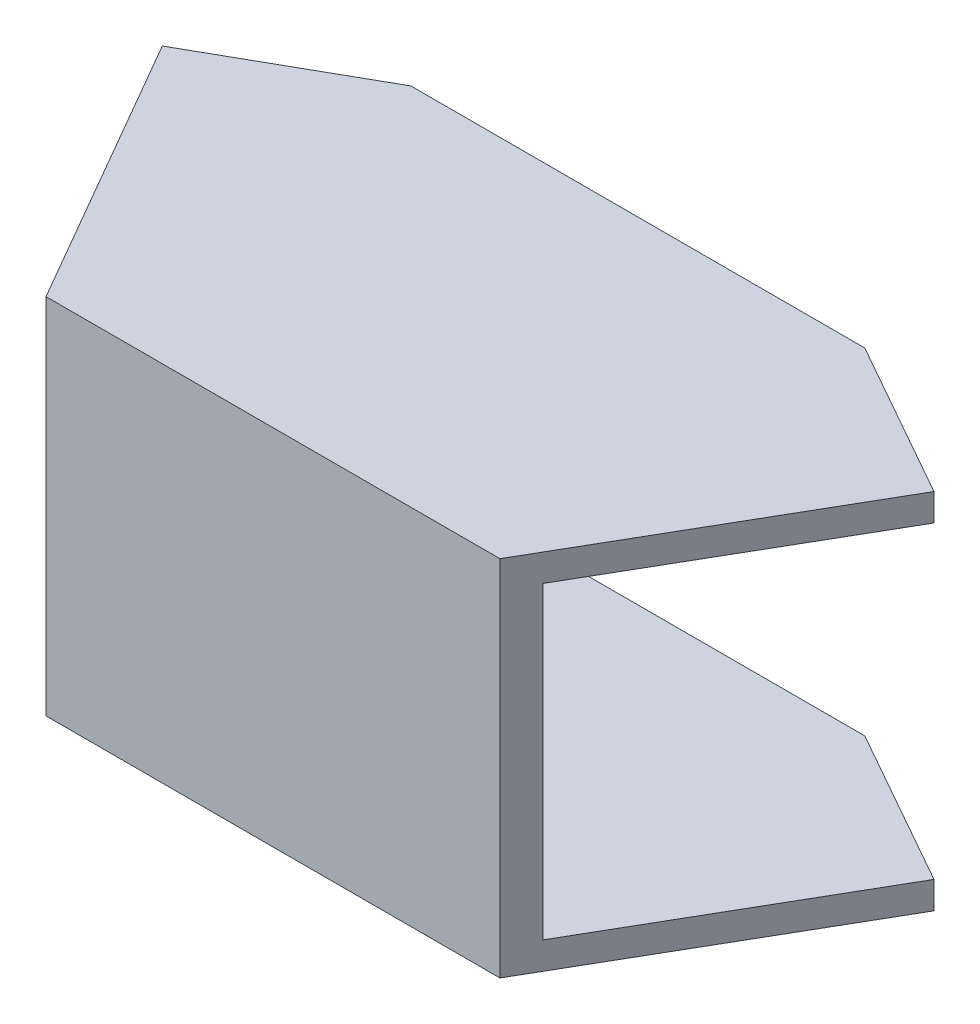
SolidWorks part; units mm, degrees
material "可锻铸铁"
ref_plane "前视" through (0, 0, 0) normal (0, 0, 1) x (1, 0, 0)
ref_plane "上视" through (0, 0, 0) normal (0, 1, 0) x (1, 0, 0)
ref_plane "右视" through (0, 0, 0) normal (1, 0, 0) x (0, 0, -1)
sketch "草图1" plane through (0, 0, 0) normal (0, 1, 0) x (1, 0, 0)
  line L0 (-53.1748, 0) -> (65.5075, 0) construction
  line L1 (-25, -16.7015) -> (25, -16.7015)
  line L2 (0, 39.3205) -> (0, -37.3985) construction
  line L3 (25, -16.7015) -> (42.5, 13.6094)
  line L4 (-25, -16.7015) -> (-42.5, 13.6094)
  line L5 (-42.5, 13.6094) -> (-25, 23.4878)
  line L6 (-25, 23.4878) -> (25, 23.4878)
  line L7 (25, 23.4878) -> (42.5, 13.6094)
  dimension "D1" = 50
  dimension "D2" = 35
  dimension "D4" = 120
  dimension "D6" = 50
extrude "凸台-拉伸1" add sketch "草图1" along normal blind 40
shell "抽壳1" thickness 3
